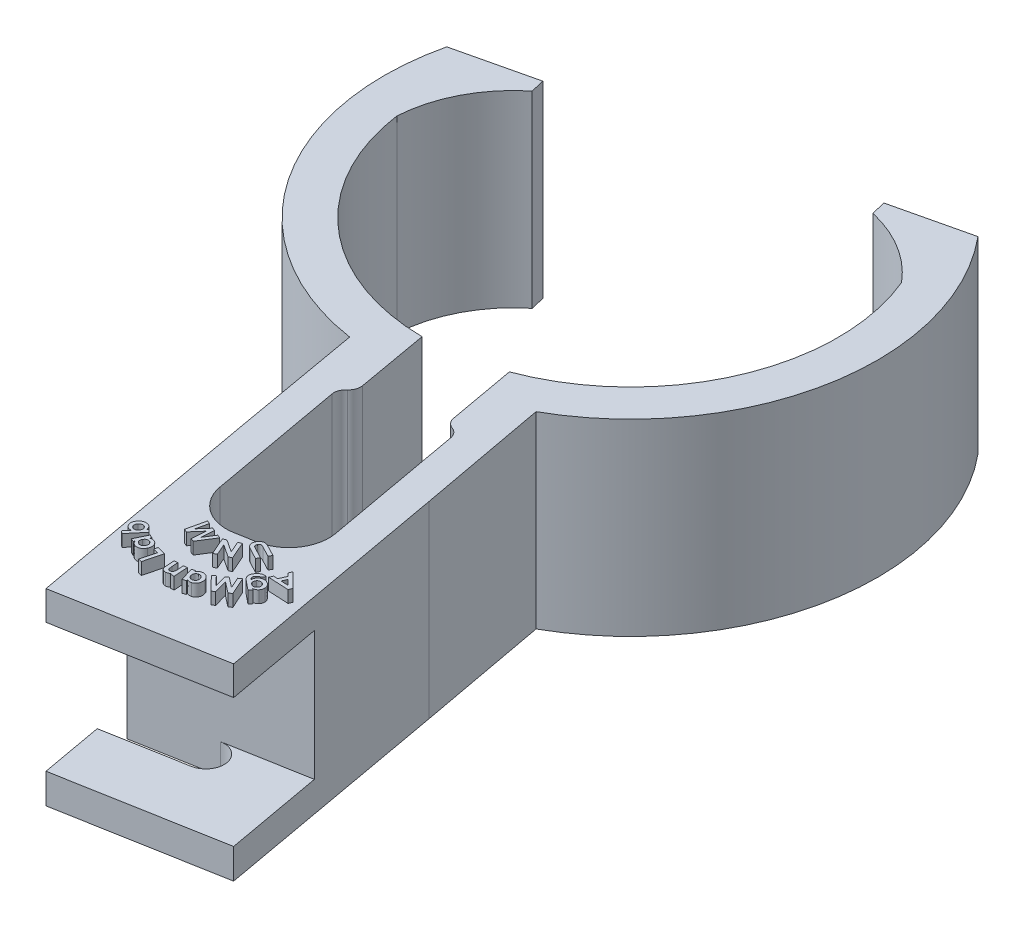
SolidWorks part; units mm, degrees
ref_plane "Front Plane" through (0, 0, 0) normal (0, 0, 1) x (1, 0, 0)
ref_plane "Top Plane" through (0, 0, 0) normal (0, 1, 0) x (1, 0, 0)
ref_plane "Right Plane" through (0, 0, 0) normal (1, 0, 0) x (0, 0, -1)
sketch "Sketch2" plane through (0, 0, 0) normal (0, 1, 0) x (1, 0, 0)
  line L3 (21.6168, -30.1234) -> (2.2072, -34.6943)
  line L8 (90.5621, -13.8869) -> (109.5831, -9.4076)
  line L10 (52.8447, -109.5826) -> (58.6016, -142.3661)
  line L12 (98.3058, -135.2117) -> (92.255, -102.4463)
  line L15 (98.3058, -135.2117) -> (104.6, -170.1422)
  line L17 (64.9796, -118.4766) -> (61.804, -100.4568)
  line L20 (104.6, -170.1422) -> (64.8958, -177.2966)
  line L22 (83.3792, -114.156) -> (80.3189, -97.1724)
  line L26 (62.9466, -124.111) -> (63.97, -129.7906)
  line L27 (87.2531, -118.7378) -> (88.4499, -125.3795)
  line L28 (64.8958, -177.2966) -> (58.6016, -142.3661)
  line L29 (88.4499, -125.3795) -> (93.5833, -153.8682)
  line L31 (85.5152, -165.4831) -> (80.7183, -166.3474)
  line L32 (63.97, -129.7906) -> (69.1034, -158.2793)
  line L33 (21.6168, -30.1234) -> (22.4332, -33.5904)
  line L34 (91.4082, -17.4799) -> (90.5621, -13.8869)
  arc A1 (10.9267, -55.8915) -> (61.804, -100.4568) centre (62.1734, -48.7107) ccw
  arc A3 (2.2072, -34.6943) -> (52.8447, -109.5826) centre (62.1734, -48.7107) ccw
  arc A4 (92.255, -102.4463) -> (109.5831, -9.4076) centre (62.1734, -48.7107) ccw
  arc A5 (83.3792, -114.156) -> (85.3162, -116.4469) centre (86.3317, -113.624) ccw
  arc A6 (80.3189, -97.1724) -> (109.9727, -28.8857) centre (62.1734, -48.7107) ccw
  arc A7 (64.9796, -118.4766) -> (63.9621, -121.2881) centre (62.0251, -118.9972) cw
  arc A10 (62.9466, -124.111) -> (63.9621, -121.2881) centre (65.899, -123.579) cw
  arc A11 (87.2531, -118.7378) -> (85.3162, -116.4469) centre (84.3007, -119.2698) ccw
  arc A12 (109.9727, -28.8857) -> (91.4082, -17.4799) centre (83.6607, -50.9009) ccw
  arc A13 (22.4332, -33.5904) -> (10.9267, -55.8915) centre (41.8498, -57.7277) ccw
  arc A14 (69.1034, -158.2793) -> (80.7183, -166.3474) centre (78.9449, -156.5059) ccw
  arc A15 (85.5152, -165.4831) -> (93.5833, -153.8682) centre (83.7418, -155.6416) ccw
  point P1 (0, 0)
  point P2 (0, 0)
  point P4 (0, 0)
  point P6 (0, 0)
  point P7 (0, 0)
  point P8 (0, 0)
  point P10 (0, 0)
  point P11 (0, 0)
  point P13 (0, 0)
  point P20 (0, 0)
  point P50 (58.6016, -142.3661)
  point P53 (98.3058, -135.2117)
  dimension "D2" = 10
  dimension "D1" = 10
extrude "Boss-Extrude6" add sketch "Sketch2" along normal blind 47
sketch "Sketch13" plane through (32.9835, 0, 183.0469) normal (0.1773, 0, 0.9842) x (0.9842, 0, -0.1773)
  line L0 (32.4263, 47) -> (32.4263, 39.7)
  line L1 (32.4263, 47) -> (72.7699, 47)
  line L2 (32.4263, 0) -> (72.7699, 0)
  line L3 (72.7699, 47) -> (72.7699, 39.7)
  line L4 (32.4263, 7.5) -> (72.7699, 7.5)
  line L5 (32.4263, 39.7) -> (72.7699, 39.7)
  line L6 (32.4263, 7.5) -> (32.4263, 0)
  line L7 (72.7699, 7.5) -> (72.7699, 0)
  line L8 (72.7699, 47) -> (72.7699, 0) construction
  line L9 (32.4263, 47) -> (32.4263, 0) construction
  line L10 (61.8138, 0) -> (63.3138, 0) construction
  line L12 (63.3138, 47) -> (61.8138, 47) construction
  line M9 (32.4263, 0) -> (72.7699, 0)
  line M10 (72.7699, 0) -> (72.7699, 47)
  line M12 (32.4263, 47) -> (32.4263, 0)
  dimension "D1" = 32.2
extrude "Boss-Extrude7" add sketch "Sketch13" along normal blind 25 contours L4 M12 M9 M10 | L1 L3 L5 L0
sketch "Sketch14" plane through (0, 7.5, 0) normal (0, 1, 0) x (1, 0, 0)
  line L0 (64.8958, -177.2966) -> (84.7479, -173.7194)
  line L1 (64.8958, -177.2966) -> (104.6, -170.1422) construction
  line L3 (86.3696, -182.7194) -> (66.5175, -186.2966)
  line L4 (69.3292, -201.9003) -> (64.8958, -177.2966) construction
  line L5 (66.5175, -186.2966) -> (64.8958, -177.2966)
  arc A0 (86.3696, -182.7194) -> (84.7479, -173.7194) centre (85.5588, -178.2194) ccw
extrude "Cut-Extrude4" cut sketch "Sketch14" against normal blind 25 contours L0 A0 L3 L5
sketch "Sketch15" plane through (0, 47, 0) normal (0, 1, 0) x (1, 0, 0)
  arc A0 (100.0011, -168.5333) -> (70.5868, -177.857) centre (82.8811, -165.5832) cw construction
  text T0 "<b> AgMan Lab</b>\r\n<b>UNM</b>" font "Century Gothic" height in points 18
  point P3 (88.1304, -182.1434)
extrude "Boss-Extrude8" add sketch "Sketch15" along normal blind 3
sketch "Sketch16" plane through (0, 0, 0) normal (0, -1, 0) x (-1, 0, 0)
  arc A0 (-69.1755, -189.9245) -> (-105.6115, -182.617) centre (-45.3948, 23.1394) cw construction
  text T0 "<b>ZED</b>" font "Century Gothic" height in points 36
extrude "Cut-Extrude6" cut sketch "Sketch16" against normal blind 1
